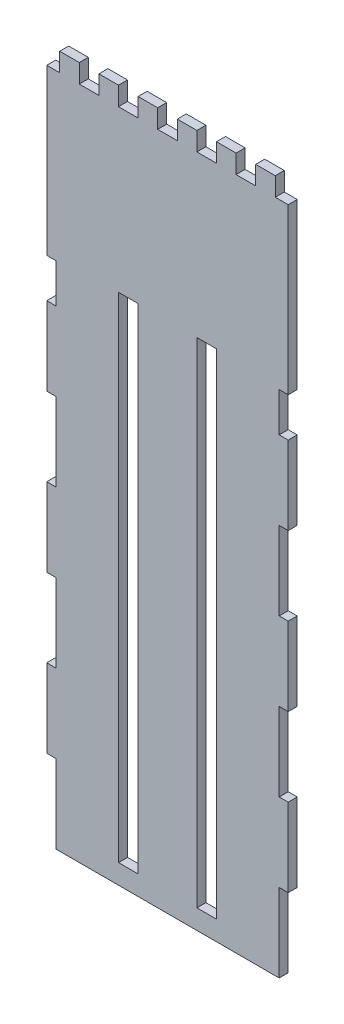
SolidWorks part; units mm, degrees
ref_plane "Front Plane" through (0, 0, 0) normal (0, 0, 1) x (1, 0, 0)
ref_plane "Top Plane" through (0, 0, 0) normal (0, 1, 0) x (1, 0, 0)
ref_plane "Right Plane" through (0, 0, 0) normal (1, 0, 0) x (0, 0, -1)
sketch "Sketch1" plane through (0, 0, 0) normal (0, 0, 1) x (1, 0, 0)
  line L1 (-39.116, 109.22) -> (39.116, 109.22)
  line L2 (-39.116, 109.22) -> (-39.116, -109.22)
  line L3 (-39.116, -109.22) -> (39.116, -109.22)
  line L4 (39.116, 109.22) -> (39.116, -109.22)
  point P4 (0, 109.22)
  point P7 (-39.116, 0)
  dimension "D1" = 78.232
  dimension "D2" = 218.44
extrude "Boss-Extrude1" add sketch "Sketch1" along normal mid plane 2.921
sketch "Sketch2" plane through (0, 0, 1.4605) normal (0, 0, 1) x (1, 0, 0)
  line L0 (-36.195, -109.22) -> (36.195, -109.22)
  line L1 (-39.116, 109.22) -> (39.116, 109.22)
  line L2 (-39.116, 109.22) -> (-39.116, -109.22)
  line L3 (-39.116, -109.22) -> (-36.195, -109.22)
  line L4 (39.116, 109.22) -> (39.116, -109.22)
  line L5 (-39.116, 109.22) -> (-36.195, 109.22)
  line L6 (-39.116, 109.22) -> (-39.116, -109.22)
  line L7 (-39.116, -109.22) -> (-36.195, -109.22)
  line L8 (-36.195, 109.22) -> (-36.195, -109.22)
  line L9 (39.116, -109.22) -> (36.195, -109.22)
  line L10 (39.116, -109.22) -> (39.116, 109.22)
  line L11 (39.116, 109.22) -> (36.195, 109.22)
  line L12 (36.195, -109.22) -> (36.195, 109.22)
  line L13 (36.195, -109.22) -> (39.116, -109.22)
  line L14 (-39.116, -83.82) -> (-36.195, -83.82)
  line L15 (39.116, -83.82) -> (36.195, -83.82)
  line L16 (-39.116, -58.42) -> (-36.195, -58.42)
  line L17 (39.116, -58.42) -> (36.195, -58.42)
  line L18 (-39.116, -33.02) -> (-36.195, -33.02)
  line L19 (39.116, -33.02) -> (36.195, -33.02)
  line L20 (-39.116, -7.62) -> (-36.195, -7.62)
  line L21 (39.116, -7.62) -> (36.195, -7.62)
  line L22 (-39.116, 17.78) -> (-36.195, 17.78)
  line L23 (39.116, 17.78) -> (36.195, 17.78)
  line L24 (-39.116, 43.18) -> (-36.195, 43.18)
  line L25 (39.116, 43.18) -> (36.195, 43.18)
  line L26 (-39.116, -109.22) -> (-39.116, -83.82) construction
  line L27 (-39.116, 55.88) -> (39.116, 55.88)
  point P40 (-37.6555, 43.18)
  line M28 (-39.116, -109.22) -> (39.116, -109.22)
  line M29 (39.116, -109.22) -> (39.116, 109.22)
  dimension "D1" = 2.921
  dimension "D2" = 2.921
  dimension "D4" = 25.4
  dimension "D5" = 2.921
  dimension "D6" = 12.7
  dimension "D3" = 7
extrude "Cut-Extrude1" cut sketch "Sketch2" against normal blind 2.921 contours L14 L6 L8 M28 | L18 L6 L16 L8 | L22 L6 L20 L8 | L27 L6 L24 L8 | L27 L12 L25 M29 | L23 L12 L21 M29 | L15 L12 M29 M28 | L19 L12 L17 M29
sketch "Sketch3" plane through (0, 109.22, 0) normal (0, 1, 0) x (1, 0, 0)
  line L0 (39.116, 1.4605) -> (-39.116, 1.4605) construction
  line L1 (34.925, 1.4605) -> (28.575, 1.4605)
  line L2 (34.925, 1.4605) -> (34.925, -1.4605)
  line L3 (34.925, -1.4605) -> (28.575, -1.4605)
  line L4 (28.575, 1.4605) -> (28.575, -1.4605)
  line L5 (39.116, -1.4605) -> (-39.116, -1.4605) construction
  line L6 (39.116, -1.4605) -> (39.116, 1.4605) construction
  line L7 (22.225, 1.4605) -> (22.225, -1.4605)
  line L8 (22.225, 1.4605) -> (15.875, 1.4605)
  line L9 (15.875, 1.4605) -> (15.875, -1.4605)
  line L10 (22.225, -1.4605) -> (15.875, -1.4605)
  line L11 (9.525, 1.4605) -> (9.525, -1.4605)
  line L12 (9.525, 1.4605) -> (3.175, 1.4605)
  line L13 (3.175, 1.4605) -> (3.175, -1.4605)
  line L14 (9.525, -1.4605) -> (3.175, -1.4605)
  line L15 (-3.175, 1.4605) -> (-3.175, -1.4605)
  line L16 (-3.175, 1.4605) -> (-9.525, 1.4605)
  line L17 (-9.525, 1.4605) -> (-9.525, -1.4605)
  line L18 (-3.175, -1.4605) -> (-9.525, -1.4605)
  line L19 (-15.875, 1.4605) -> (-15.875, -1.4605)
  line L20 (-15.875, 1.4605) -> (-22.225, 1.4605)
  line L21 (-22.225, 1.4605) -> (-22.225, -1.4605)
  line L22 (-15.875, -1.4605) -> (-22.225, -1.4605)
  line L23 (-28.575, 1.4605) -> (-28.575, -1.4605)
  line L24 (-28.575, 1.4605) -> (-34.925, 1.4605)
  line L25 (-34.925, 1.4605) -> (-34.925, -1.4605)
  line L26 (-28.575, -1.4605) -> (-34.925, -1.4605)
  line L27 (34.925, 1.4605) -> (22.225, 1.4605) construction
  point P10 (28.575, 0)
  dimension "D1" = 4.191
  dimension "D2" = 6.35
  dimension "D4" = 12.7
  dimension "D3" = 6
extrude "Boss-Extrude2" add sketch "Sketch3" along normal blind 6.0452
sketch "Sketch5" plane through (0, 0, 1.4605) normal (0, 0, 1) x (1, 0, 0)
  line L0 (0, 109.22) -> (0, -109.22) construction
  line L1 (-15.875, 57.15) -> (-9.525, 57.15)
  line L2 (-15.875, 57.15) -> (-15.875, -102.87)
  line L3 (-15.875, -102.87) -> (-9.525, -102.87)
  line L4 (-9.525, 57.15) -> (-9.525, -102.87)
  line L5 (9.525, 57.15) -> (15.875, 57.15)
  line L6 (9.525, 57.15) -> (9.525, -102.87)
  line L7 (9.525, -102.87) -> (15.875, -102.87)
  line L8 (15.875, 57.15) -> (15.875, -102.87)
  line L9 (3.175, 109.22) -> (-3.175, 109.22) construction
  line L10 (-36.195, -109.22) -> (36.195, -109.22) construction
  line L11 (-9.525, 109.22) -> (-15.875, 109.22) construction
  line L12 (-9.525, 57.15) -> (9.525, 57.15) construction
  point P16 (0, 57.15)
  dimension "D1" = 31.75
  dimension "D2" = 52.07
  dimension "D3" = 6.35
  dimension "D4" = 6.35
extrude "Cut-Extrude2" cut sketch "Sketch5" against normal through all
